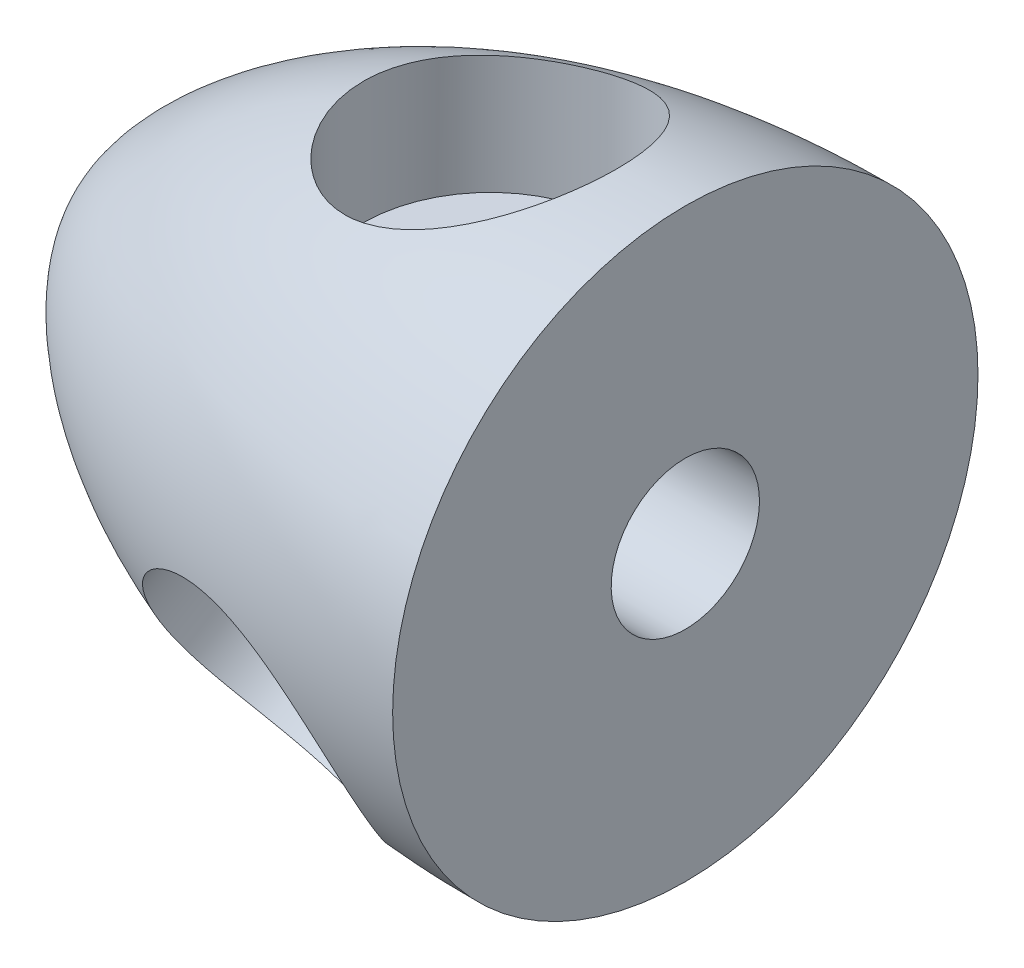
SolidWorks part; units mm, degrees
ref_plane "Front Plane" through (0, 0, 0) normal (0, 0, 1) x (1, 0, 0)
ref_plane "Top Plane" through (0, 0, 0) normal (0, 1, 0) x (1, 0, 0)
ref_plane "Right Plane" through (0, 0, 0) normal (1, 0, 0) x (0, 0, -1)
sketch "Sketch1" plane through (0, 0, 0) normal (0, 0, 1) x (1, 0, 0)
  line L0 (0, 19.05) -> (0, 0)
  line L1 (0, 0) -> (-38.1, 0)
  line L2 (-6.1448, 19.05) -> (6.1448, 19.05) construction
  line L3 (-38.1, -5.0533) -> (-38.1, 5.0533) construction
  spline S0 degree 3 poles (0, 19.05) (-25.41, 19.05) (-38.1, 6.3167) (-38.1, 0) knots 0 0 0 0 1 1 1 1
  dimension "D1" = 18.95
  dimension "D2" = 76.23
  dimension "D3" = 38.1
  dimension "D4" = 19.05
revolve "Revolve2" add sketch "Sketch1" angle 360 about L1
ref_plane "Plane1" through (0, 19.05, 0) normal (0, 1, 0) x (1, 0, 0)
sketch "Sketch2" plane through (0, 19.05, 0) normal (0, 1, 0) x (1, 0, 0)
  line L0 (-12.7, 0) -> (0, 0) construction
  circle A0 centre (-12.7, 0) radius 8.255
  dimension "D2" = 16.51
  dimension "D1" = 12.7
extrude "Cut-Extrude1" cut sketch "Sketch2" against normal blind 11.43
pattern_circular "CirPattern5" count 3 over 360 about axis through (0, 0, 0) along (1, 0, 0) of "Cut-Extrude1"
sketch "Sketch3" plane through (0, 0, 0) normal (1, 0, 0) x (0, 0, -1)
  circle A0 centre (0, 0) radius 4.826
  dimension "D1" = 9.652
extrude "Cut-Extrude2" cut sketch "Sketch3" against normal blind 12.7
